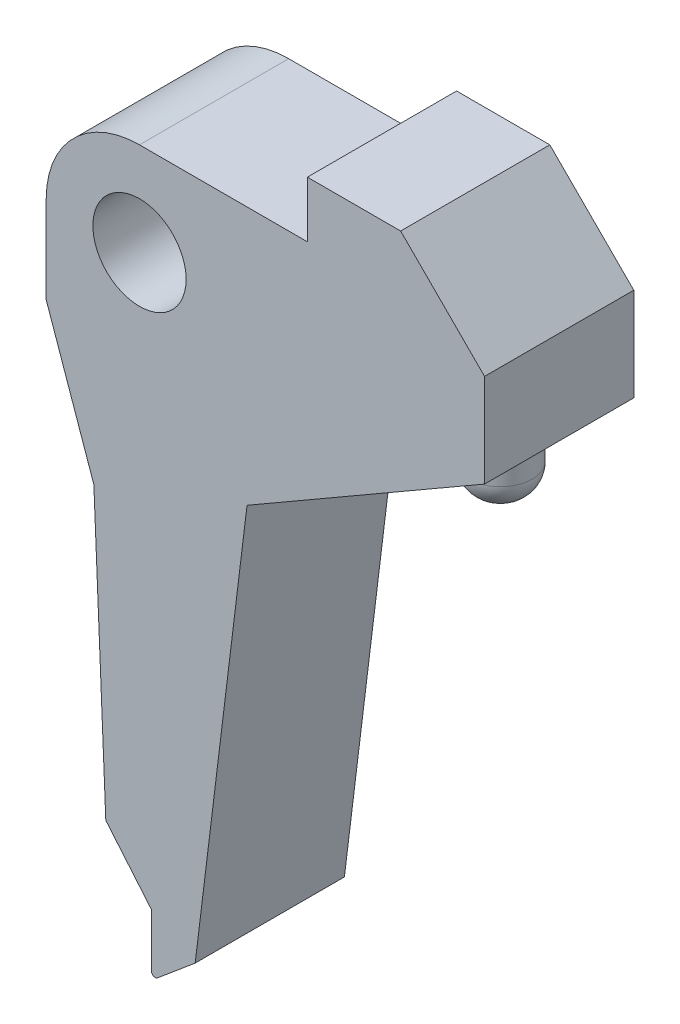
SolidWorks part; units mm, degrees
ref_plane "정면" through (0, 0, 0) normal (0, 0, 1) x (1, 0, 0)
ref_plane "윗면" through (0, 0, 0) normal (0, 1, 0) x (1, 0, 0)
ref_plane "우측면" through (0, 0, 0) normal (1, 0, 0) x (0, 0, -1)
sketch "스케치1" plane through (0, 0, 0) normal (0, 0, 1) x (1, 0, 0)
  line L0 (0, 5) -> (9, 5)
  line L1 (9, 5) -> (9, 8)
  line L2 (9, 8) -> (14, 8)
  line L3 (14, 8) -> (18.5, 3.5)
  line L4 (18.5, 3.5) -> (18.5, -1.5)
  line L5 (18.5, -1.5) -> (5.7663, -8.8518)
  line L6 (5.7663, -8.8518) -> (2.9854, -31.5)
  line L7 (2.9854, -31.5) -> (0.9682, -33.193)
  line L8 (0.6396, -33.0398) -> (0.6396, -30.1837)
  line L9 (0.6396, -30.1837) -> (-1.8057, -27.2695)
  line L10 (-1.8057, -27.2695) -> (-2.4456, -12)
  line L11 (-2.4456, -12) -> (-5, -4.6966)
  line L12 (-5, -4.6966) -> (-5, 0)
  line L13 (18.5, -1.5) -> (3.5201, -1.5) construction
  line L14 (2.9854, -31.5) -> (2.9854, -0.7863) construction
  line L15 (18.5, 3.5) -> (6.1947, 3.5) construction
  line L16 (-1.8057, -27.2695) -> (1.5473, -27.2695) construction
  circle A0 centre (0, 0) radius 2.5
  arc A1 (0, 5) -> (-5, 0) centre (0, 0) ccw
  arc A2 (0.9682, -33.193) -> (0.6396, -33.0398) centre (0.8396, -33.0398) cw
  dimension "D1" = 5
  dimension "D2" = 10
  dimension "D3" = 0.2
  dimension "D5" = 9
  dimension "D6" = 5
  dimension "D7" = 5
  dimension "D8" = 30
  dimension "D9" = 7
  dimension "D11" = 45
  dimension "D13" = 50
  dimension "D14" = 12
  dimension "D15" = 3
  dimension "D16" = 4.5
extrude "보스-돌출1" add sketch "스케치1" along normal blind 8
ref_plane "평면1" through (0, -1.5, 0) normal (0, 1, 0) x (1, 0, 0)
sketch "스케치3" plane through (0, -1.5, 0) normal (0, 1, 0) x (1, 0, 0)
  line L1 (18.5, -4) -> (12.1992, -4) construction
  line L3 (18.5, -8) -> (18.5, 0) construction
  line L4 (5.8984, -8) -> (18.5, 0) construction
  circle A0 centre (15.3496, -4) radius 2.5
  dimension "D1" = 5
extrude "컷-돌출1" cut sketch "스케치3" against normal up to next
sketch "스케치4" plane through (0, -1.5, 0) normal (0, -1, 0) x (1, 0, 0)
  circle A0 centre (15.3496, 4) radius 1.7
  dimension "D1" = 3.4
extrude "보스-돌출2" add sketch "스케치4" along normal blind 4
fillet "필렛1" radius 1.5 1 edges at (15.3496, -5.5, 2.3)
